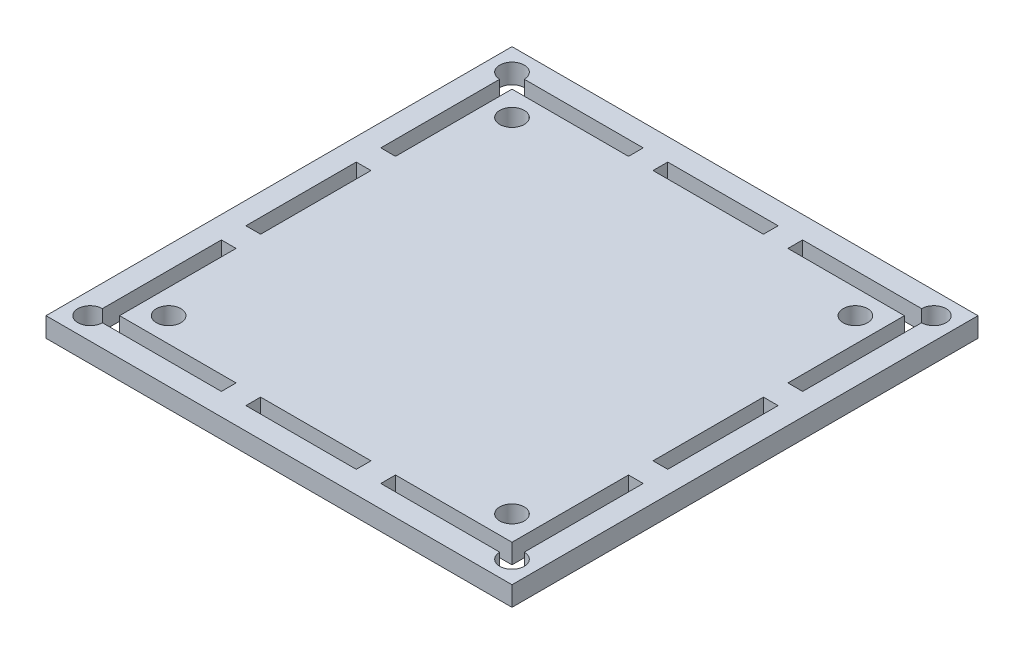
SolidWorks part; units mm, degrees
ref_plane "Front Plane" through (0, 0, 0) normal (0, 0, 1) x (1, 0, 0)
ref_plane "Top Plane" through (0, 0, 0) normal (0, 1, 0) x (1, 0, 0)
ref_plane "Right Plane" through (0, 0, 0) normal (1, 0, 0) x (0, 0, -1)
ref_plane "Plane1" through (0, 0, 0) normal (0, -1, 0) x (1, 0, 0)
sketch "Sketch1" plane through (0, 0, 0) normal (0, -1, 0) x (1, 0, 0)
  line L0 (6.5, 17.2) -> (16.2, 17.2)
  line L1 (17.2, 16.2) -> (17.2, 6.5)
  line L2 (17.2, 6.5) -> (16, 6.5)
  line L3 (16, 6.5) -> (16, 16)
  line L4 (16, 16) -> (6.5, 16)
  line L5 (6.5, 16) -> (6.5, 17.2)
  line L6 (-6.5, -17.2) -> (-16.2, -17.2)
  line L7 (-17.2, -16.2) -> (-17.2, -6.5)
  line L8 (-17.2, -6.5) -> (-16, -6.5)
  line L9 (-16, -6.5) -> (-16, -16)
  line L10 (-16, -16) -> (-6.5, -16)
  line L11 (-6.5, -16) -> (-6.5, -17.2)
  line L12 (-4.5, 17.2) -> (4.5, 17.2)
  line L13 (4.5, 17.2) -> (4.5, 16)
  line L14 (4.5, 16) -> (-4.5, 16)
  line L15 (-4.5, 16) -> (-4.5, 17.2)
  line L16 (6.5, -16) -> (16, -16)
  line L17 (16, -16) -> (16, -6.5)
  line L18 (16, -6.5) -> (17.2, -6.5)
  line L19 (17.2, -6.5) -> (17.2, -16.2)
  line L20 (16.2, -17.2) -> (6.5, -17.2)
  line L21 (6.5, -17.2) -> (6.5, -16)
  line L22 (-16, -4.5) -> (-17.2, -4.5)
  line L23 (-17.2, -4.5) -> (-17.2, 4.5)
  line L24 (-17.2, 4.5) -> (-16, 4.5)
  line L25 (-16, 4.5) -> (-16, -4.5)
  line L26 (16, 4.5) -> (17.2, 4.5)
  line L27 (17.2, 4.5) -> (17.2, -4.5)
  line L28 (17.2, -4.5) -> (16, -4.5)
  line L29 (16, -4.5) -> (16, 4.5)
  line L30 (-16, 16) -> (-16, 6.5)
  line L31 (-16, 6.5) -> (-17.2, 6.5)
  line L32 (-17.2, 6.5) -> (-17.2, 16.2)
  line L33 (-16.2, 17.2) -> (-6.5, 17.2)
  line L34 (-6.5, 17.2) -> (-6.5, 16)
  line L35 (-6.5, 16) -> (-16, 16)
  line L36 (-4.5, -17.2) -> (-4.5, -16)
  line L37 (-4.5, -16) -> (4.5, -16)
  line L38 (4.5, -16) -> (4.5, -17.2)
  line L39 (4.5, -17.2) -> (-4.5, -17.2)
  line L40 (19, 19) -> (-19, 19)
  line L41 (-19, 19) -> (-19, -19)
  line L42 (-19, -19) -> (19, -19)
  line L43 (19, -19) -> (19, 19)
  line L44 (0, 20.5223) -> (0, -19.8785) construction
  line L45 (19, -19) -> (-19, 19) construction
  line L46 (24.7668, 0) -> (-29.7708, 0) construction
  arc A0 (16.2, 17.2) -> (17.2, 16.2) centre (17.2, 17.2) cw
  circle A1 centre (-14, -14) radius 1
  circle A2 centre (-14, 14) radius 1
  circle A3 centre (14, -14) radius 1
  circle A4 centre (14, 14) radius 1
  arc A5 (-16.2, -17.2) -> (-17.2, -16.2) centre (-17.2, -17.2) cw
  arc A6 (17.2, -16.2) -> (16.2, -17.2) centre (17.2, -17.2) cw
  arc A7 (-17.2, 16.2) -> (-16.2, 17.2) centre (-17.2, 17.2) cw
  point P65 (-29.7708, 0)
  point P66 (0, 0)
  point P67 (0, -16)
  point P68 (0, -17.2)
  point P69 (0, -19.8785)
  point P70 (0, 0)
  dimension "D4" = 2
  dimension "D6" = 1
  dimension "D1" = 1.2
  dimension "D2" = 38
  dimension "D3" = 5
  dimension "D5" = 5
  dimension "D7" = 9
  dimension "D8" = 3
  dimension "D9" = 2
  dimension "D10" = 2
extrude "Boss-Extrude1" add sketch "Sketch1" against normal blind 1.6
equation "\"D10@Sketch1\"=\"D9@Sketch1\""
